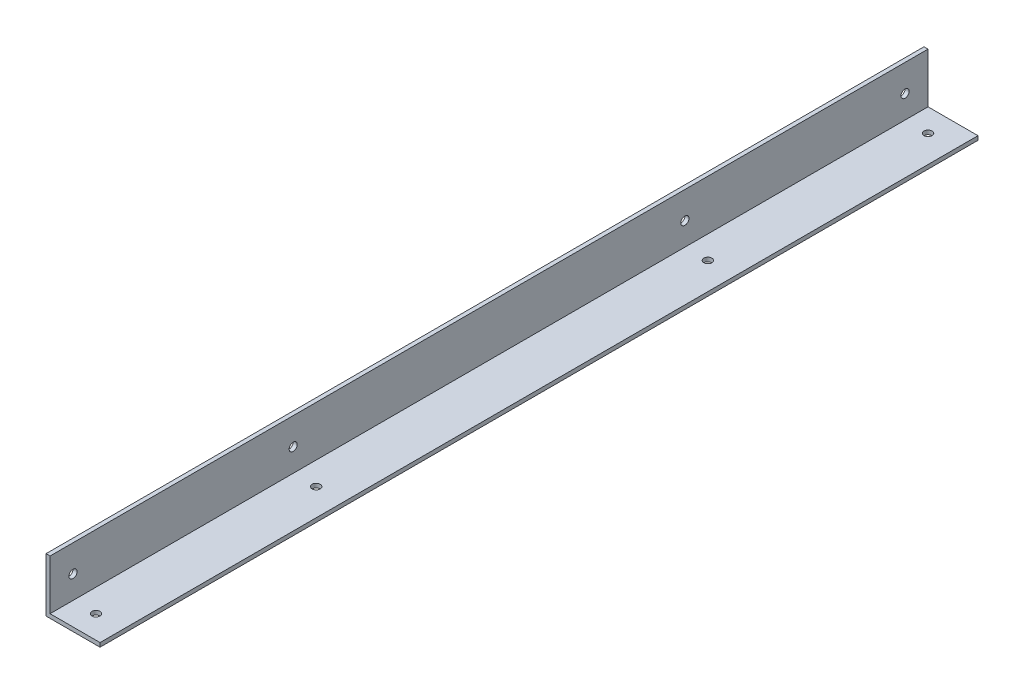
SolidWorks part; units mm, degrees
ref_plane "Plan de face" through (0, 0, 0) normal (0, 0, 1) x (1, 0, 0)
ref_plane "Plan de dessus" through (0, 0, 0) normal (0, 1, 0) x (1, 0, 0)
ref_plane "Plan de droite" through (0, 0, 0) normal (1, 0, 0) x (0, 0, -1)
sketch "Esquisse1" plane through (0, 0, 0) normal (0, 0, 1) x (1, 0, 0)
  line L0 (-17.4317, 4.7734) -> (-17.4317, -15.2266)
  line L1 (-17.4317, -15.2266) -> (2.5683, -15.2266)
  line L2 (2.5683, -15.2266) -> (2.5683, -13.7266)
  line L3 (2.5683, -13.7266) -> (-15.9317, -13.7266)
  line L4 (-15.9317, -13.7266) -> (-15.9317, 4.7734)
  line L5 (-15.9317, 4.7734) -> (-17.4317, 4.7734)
  dimension "D1" = 1.5
  dimension "D2" = 1.5
  dimension "D3" = 20
  dimension "D4" = 20
extrude "Extrusion1" add sketch "Esquisse1" along normal blind 325
sketch "Esquisse2" plane through (0, -13.7266, 0) normal (0, 1, 0) x (-1, 0, 0)
  line L0 (-2.5683, 325) -> (-2.5683, 0) construction
  line L1 (-2.5683, 325) -> (15.9317, 325) construction
  line L2 (-2.5683, 0) -> (15.9317, 0) construction
  circle A0 centre (7.4317, 8.5) radius 1.5
  circle A1 centre (7.4317, 316.5) radius 1.5
  circle A2 centre (7.4317, 235) radius 1.5
  circle A3 centre (7.4317, 90) radius 1.5
  dimension "D1" = 8.5
  dimension "D5" = 90
  dimension "D2" = 8.5
  dimension "D3" = 10
  dimension "D4" = 10
  dimension "D6" = 90
  dimension "D7" = 10
  dimension "D8" = 10
extrude "Extrusion2" cut sketch "Esquisse2" against normal blind 300
sketch "Esquisse3" plane through (-15.9317, 0, 0) normal (1, 0, 0) x (0, 0, -1)
  line L0 (-316.5, -5.2266) -> (-8.5, -5.2266) construction
  line L1 (-325, -13.7266) -> (-325, 4.7734) construction
  line L2 (0, -13.7266) -> (0, 4.7734) construction
  line L3 (-325, 4.7734) -> (0, 4.7734) construction
  circle A0 centre (-316.5, -5.2266) radius 1.5
  circle A1 centre (-8.5, -5.2266) radius 1.5
  circle A2 centre (-235, -5.2266) radius 1.5
  circle A3 centre (-90, -5.2266) radius 1.5
  point P14 (-325, -4.4766)
  dimension "D1" = 8.5
  dimension "D4" = 90
  dimension "D2" = 8.5
  dimension "D3" = 10
  dimension "D5" = 90
extrude "Extrusion3" cut sketch "Esquisse3" against normal blind 300
